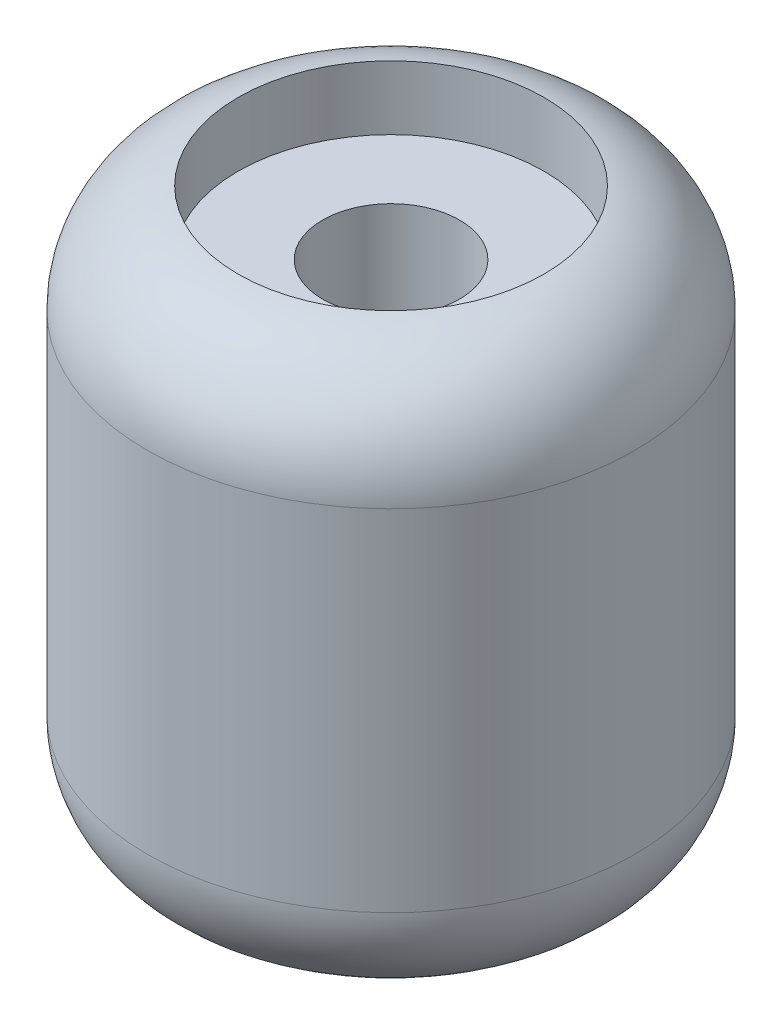
SolidWorks part; units mm, degrees
material "PP homopolímero"
ref_plane "Alzado" through (0, 0, 0) normal (0, 0, 1) x (1, 0, 0)
ref_plane "Planta" through (0, 0, 0) normal (0, 1, 0) x (1, 0, 0)
ref_plane "Vista lateral" through (0, 0, 0) normal (1, 0, 0) x (0, 0, -1)
sketch "Croquis1" plane through (0, 0, 0) normal (0, 0, 1) x (1, 0, 0)
  line L0 (0, 13) -> (0, -13) construction
  line L1 (-3.1342, -13) -> (-6.1342, -13)
  line L2 (-11.1342, -8) -> (-11.1342, 8)
  line L3 (-6.1342, 13) -> (-3.1342, 13)
  line L5 (-3.1342, 13) -> (-3.1342, -13)
  arc A0 (-6.1342, -13) -> (-11.1342, -8) centre (-6.1342, -8) cw
  arc A1 (-11.1342, 8) -> (-6.1342, 13) centre (-6.1342, 8) cw
  point P2 (-11.1342, -13)
  point P4 (0, 0)
  point P11 (-11.1342, 13)
  point P12 (-3.1342, 0)
  dimension "D3" = 5
  dimension "D1" = 8
  dimension "D2" = 26
revolve "Revolución1" add sketch "Croquis1" angle 360 about L0
ref_plane "Plano1" through (0, 23, 0) normal (0, 1, 0) x (1, 0, 0)
sketch "Croquis3" plane through (0, 23, 0) normal (0, 1, 0) x (1, 0, 0)
  circle A0 centre (0, 0) radius 7
  circle A1 centre (0, 0) radius 3.1342
  dimension "D1" = 14
extrude "Cortar-Extruir1" cut sketch "Croquis3" against normal blind 13
